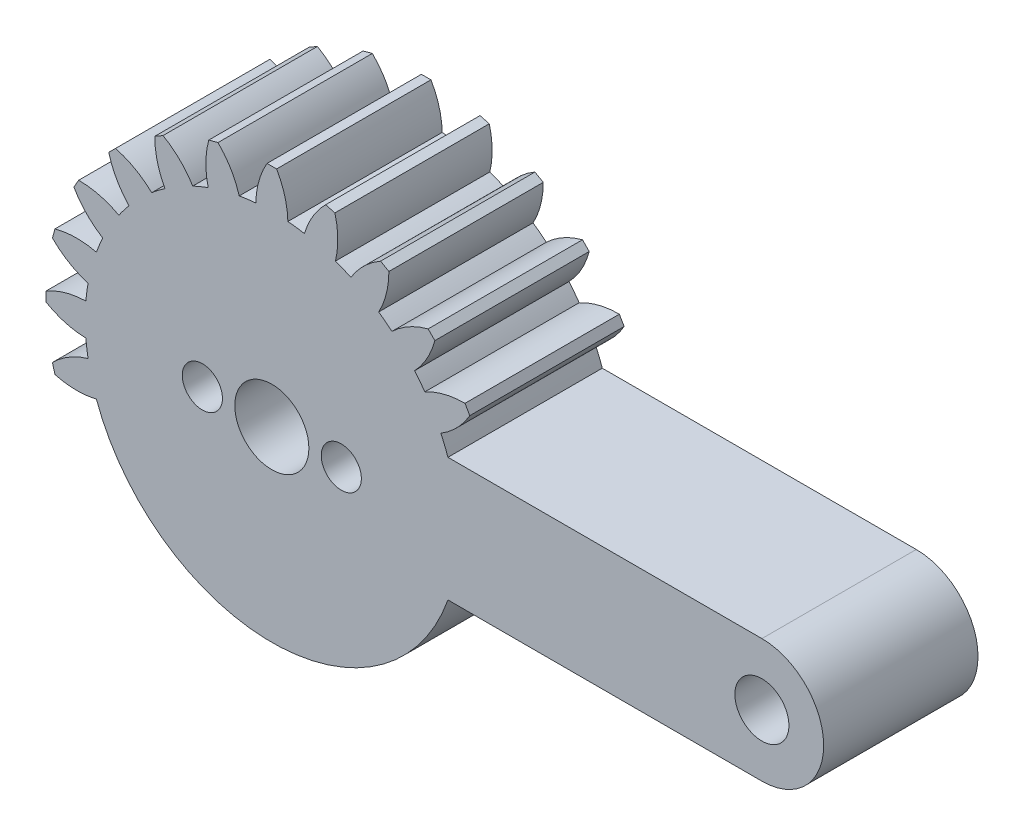
SolidWorks part; units mm, degrees
ref_plane "Front Plane" through (0, 0, 0) normal (0, 0, 1) x (1, 0, 0)
ref_plane "Top Plane" through (0, 0, 0) normal (0, 1, 0) x (1, 0, 0)
ref_plane "Right Plane" through (0, 0, 0) normal (1, 0, 0) x (0, 0, -1)
sketch "Sketch1" plane through (0, 0, 0) normal (0, 0, 1) x (1, 0, 0)
  line L0 (0, 0) -> (31.75, 0) construction
  line L1 (0, 14.63) -> (0, -14.63) construction
  line L2 (-0.31, 14.63) -> (0.31, 14.63)
  line L3 (3.4871, 14.2117) -> (4.086, 14.0513)
  line L4 (7.0465, 12.825) -> (7.5835, 12.515)
  line L5 (10.1258, 10.5642) -> (10.5642, 10.1258)
  line L6 (12.515, 7.5835) -> (12.825, 7.0465)
  line L7 (14.0513, 4.086) -> (14.2117, 3.4871)
  line L8 (14.63, 0.31) -> (14.63, -0.31)
  line L9 (14.2117, -3.4871) -> (14.0513, -4.086)
  line L10 (12.825, -7.0465) -> (12.515, -7.5835)
  line L11 (10.5642, -10.1258) -> (10.1258, -10.5642)
  line L12 (7.5835, -12.515) -> (7.0465, -12.825)
  line L13 (4.086, -14.0513) -> (3.4871, -14.2117)
  line L14 (0.31, -14.63) -> (-0.31, -14.63)
  line L15 (-3.4871, -14.2117) -> (-4.086, -14.0513)
  line L16 (-7.0465, -12.825) -> (-7.5835, -12.515)
  line L17 (-10.1258, -10.5642) -> (-10.5642, -10.1258)
  line L18 (-12.515, -7.5835) -> (-12.825, -7.0465)
  line L19 (-14.0513, -4.086) -> (-14.2117, -3.4871)
  line L20 (-14.63, -0.31) -> (-14.63, 0.31)
  line L21 (-14.2117, 3.4871) -> (-14.0513, 4.086)
  line L22 (-12.825, 7.0465) -> (-12.515, 7.5835)
  line L23 (-10.5642, 10.1258) -> (-10.1258, 10.5642)
  line L24 (-7.5835, 12.515) -> (-7.0465, 12.825)
  line L25 (-4.086, 14.0513) -> (-3.4871, 14.2117)
  line L26 (31.75, -4) -> (31.75, 4) construction
  line L27 (31.75, 4) -> (11.4091, 4)
  line L28 (31.75, -4) -> (11.4091, -4)
  circle A0 centre (0, 0) radius 1.75
  circle A1 centre (0, 0) radius 12.09
  circle A2 centre (31.75, 0) radius 1.75
  arc A3 (-1.04, 12.0452) -> (-0.31, 14.63) centre (4.3585, 11.9161) cw
  arc A4 (1.04, 12.0452) -> (0.31, 14.63) centre (-4.3585, 11.9161) ccw
  arc A5 (4.1221, 11.3656) -> (4.086, 14.0513) centre (-1.1258, 12.6381) ccw
  arc A6 (2.113, 11.9039) -> (3.4871, 14.2117) centre (7.294, 10.382) cw
  arc A7 (6.9233, 9.9114) -> (7.5835, 12.515) centre (2.1835, 12.4988) ccw
  arc A8 (5.1219, 10.9514) -> (7.0465, 12.825) centre (9.7326, 8.1404) cw
  arc A9 (9.2526, 7.7818) -> (10.5642, 10.1258) centre (5.344, 11.5078) ccw
  arc A10 (7.7818, 9.2526) -> (10.1258, 10.5642) centre (11.5078, 5.344) cw
  arc A11 (10.9514, 5.1219) -> (12.825, 7.0465) centre (8.1404, 9.7326) ccw
  arc A12 (9.9114, 6.9233) -> (12.515, 7.5835) centre (12.4988, 2.1835) cw
  arc A13 (11.9039, 2.113) -> (14.2117, 3.4871) centre (10.382, 7.294) ccw
  arc A14 (11.3656, 4.1221) -> (14.0513, 4.086) centre (12.6381, -1.1258) cw
  arc A15 (12.0452, -1.04) -> (14.63, -0.31) centre (11.9161, 4.3585) ccw
  arc A16 (12.0452, 1.04) -> (14.63, 0.31) centre (11.9161, -4.3585) cw
  arc A17 (11.3656, -4.1221) -> (14.0513, -4.086) centre (12.6381, 1.1258) ccw
  arc A18 (11.9039, -2.113) -> (14.2117, -3.4871) centre (10.382, -7.294) cw
  arc A19 (9.9114, -6.9233) -> (12.515, -7.5835) centre (12.4988, -2.1835) ccw
  arc A20 (10.9514, -5.1219) -> (12.825, -7.0465) centre (8.1404, -9.7326) cw
  arc A21 (7.7818, -9.2526) -> (10.1258, -10.5642) centre (11.5078, -5.344) ccw
  arc A22 (9.2526, -7.7818) -> (10.5642, -10.1258) centre (5.344, -11.5078) cw
  arc A23 (5.1219, -10.9514) -> (7.0465, -12.825) centre (9.7326, -8.1404) ccw
  arc A24 (6.9233, -9.9114) -> (7.5835, -12.515) centre (2.1835, -12.4988) cw
  arc A25 (2.113, -11.9039) -> (3.4871, -14.2117) centre (7.294, -10.382) ccw
  arc A26 (4.1221, -11.3656) -> (4.086, -14.0513) centre (-1.1258, -12.6381) cw
  arc A27 (-1.04, -12.0452) -> (-0.31, -14.63) centre (4.3585, -11.9161) ccw
  arc A28 (1.04, -12.0452) -> (0.31, -14.63) centre (-4.3585, -11.9161) cw
  arc A29 (-4.1221, -11.3656) -> (-4.086, -14.0513) centre (1.1258, -12.6381) ccw
  arc A30 (-2.113, -11.9039) -> (-3.4871, -14.2117) centre (-7.294, -10.382) cw
  arc A31 (-6.9233, -9.9114) -> (-7.5835, -12.515) centre (-2.1835, -12.4988) ccw
  arc A32 (-5.1219, -10.9514) -> (-7.0465, -12.825) centre (-9.7326, -8.1404) cw
  arc A33 (-9.2526, -7.7818) -> (-10.5642, -10.1258) centre (-5.344, -11.5078) ccw
  arc A34 (-7.7818, -9.2526) -> (-10.1258, -10.5642) centre (-11.5078, -5.344) cw
  arc A35 (-10.9514, -5.1219) -> (-12.825, -7.0465) centre (-8.1404, -9.7326) ccw
  arc A36 (-9.9114, -6.9233) -> (-12.515, -7.5835) centre (-12.4988, -2.1835) cw
  arc A37 (-11.9039, -2.113) -> (-14.2117, -3.4871) centre (-10.382, -7.294) ccw
  arc A38 (-11.3656, -4.1221) -> (-14.0513, -4.086) centre (-12.6381, 1.1258) cw
  arc A39 (-12.0452, 1.04) -> (-14.63, 0.31) centre (-11.9161, -4.3585) ccw
  arc A40 (-12.0452, -1.04) -> (-14.63, -0.31) centre (-11.9161, 4.3585) cw
  arc A41 (-11.3656, 4.1221) -> (-14.0513, 4.086) centre (-12.6381, -1.1258) ccw
  arc A42 (-11.9039, 2.113) -> (-14.2117, 3.4871) centre (-10.382, 7.294) cw
  arc A43 (-9.9114, 6.9233) -> (-12.515, 7.5835) centre (-12.4988, 2.1835) ccw
  arc A44 (-10.9514, 5.1219) -> (-12.825, 7.0465) centre (-8.1404, 9.7326) cw
  arc A45 (-7.7818, 9.2526) -> (-10.1258, 10.5642) centre (-11.5078, 5.344) ccw
  arc A46 (-9.2526, 7.7818) -> (-10.5642, 10.1258) centre (-5.344, 11.5078) cw
  arc A47 (-5.1219, 10.9514) -> (-7.0465, 12.825) centre (-9.7326, 8.1404) ccw
  arc A48 (-6.9233, 9.9114) -> (-7.5835, 12.515) centre (-2.1835, 12.4988) cw
  arc A49 (-2.113, 11.9039) -> (-3.4871, 14.2117) centre (-7.294, 10.382) ccw
  arc A50 (-4.1221, 11.3656) -> (-4.086, 14.0513) centre (1.1258, 12.6381) cw
  arc A51 (31.75, -4) -> (31.75, 4) centre (31.75, 0) ccw
  point P9 (0, 0)
  point P157 (31.75, 0)
  dimension "D2" = 24.18
  dimension "D3" = 3.5
  dimension "D5" = 5.4
  dimension "D9" = 8
  dimension "D1" = 31.75
  dimension "D4" = 29.26
  dimension "D6" = 0.31
  dimension "D7" = 1.04
  dimension "D8" = 24
extrude "Boss-Extrude1" add sketch "Sketch1" along normal blind 10 contours A1 | L28 A51 L27 L7 A13 A1 A16 L8 A15 A18 L9 A2 | A12 A1 A11 L6 | A10 A1 A9 L5 | A8 A1 A7 L4 | A6 A1 A5 L3 | A1 A4 L2 A3 | A50 A1 A49 L25 | A48 A1 A47 L24 | A46 A1 A45 L23 | A44 A1 A43 L22 | A42 A1 A41 L21 | A40 A1 A39 L20 | A38 A1 A37 L19 | A1 A13 L7 L27 | A18 A1 L28 L9 | A16 A1 A15 L8
sketch "Sketch2" plane through (0, 0, 10) normal (0, 0, 1) x (1, 0, 0)
  line L0 (4.5, 0) -> (-4.5, 0) construction
  circle A0 centre (-4.5, 0) radius 1.3
  circle A1 centre (4.5, 0) radius 1.3
  circle A2 centre (0, 0) radius 2.4
  point P5 (0, 0)
  dimension "D2" = 2.6
  dimension "D3" = 4.8
  dimension "D1" = 9
extrude "Cut-Extrude2" cut sketch "Sketch2" against normal through all
